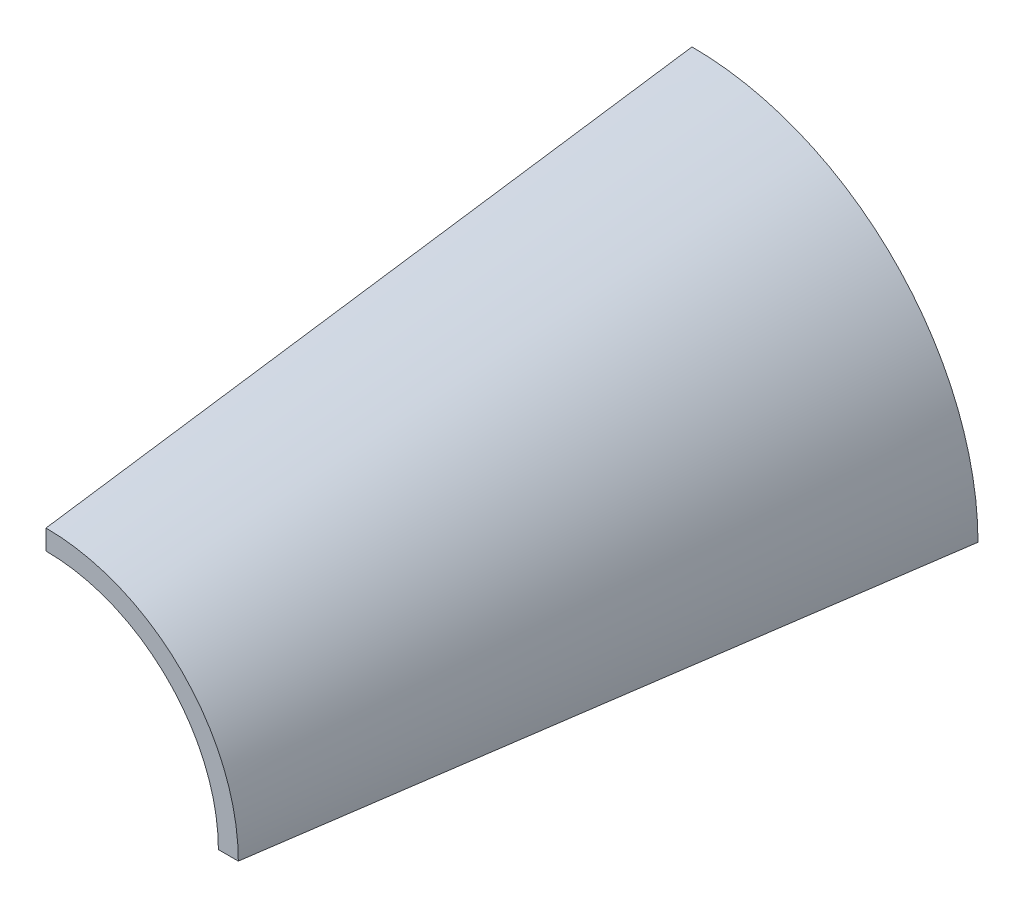
SolidWorks part; units mm, degrees
ref_plane "Piano frontale" through (0, 0, 0) normal (0, 0, 1) x (1, 0, 0)
ref_plane "Piano superiore" through (0, 0, 0) normal (0, 1, 0) x (1, 0, 0)
ref_plane "Piano destro" through (0, 0, 0) normal (1, 0, 0) x (0, 0, -1)
sketch "Schizzo1" plane through (0, 0, 0) normal (1, 0, 0) x (0, 0, -1)
  line L0 (0, 2697.9073) -> (0, 2900)
  line L1 (0, 2900) -> (-6550, 1950)
  line L2 (-6550, 1950) -> (-6550, 1747.9073)
  line L3 (-6550, 0) -> (0, 0)
  line L7 (-6550, 1747.9073) -> (0, 2697.9073)
  dimension "D1" = 2900
  dimension "D2" = 6550
  dimension "D3" = 1950
revolve "Rivoluzione1" add sketch "Schizzo1" angle 90 about L3
